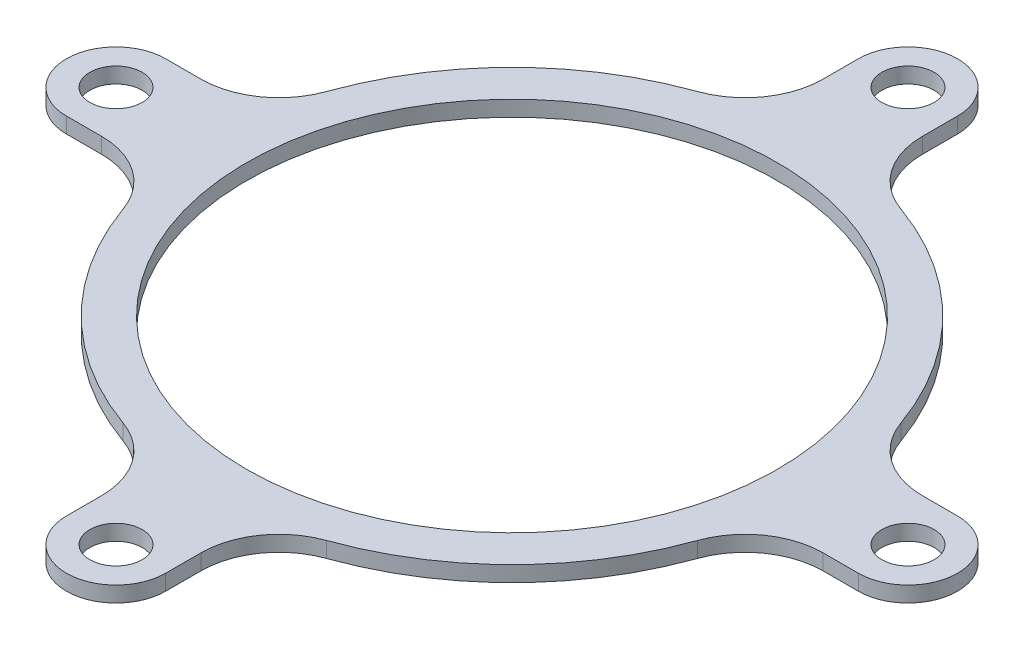
SolidWorks part; units mm, degrees
ref_plane "Front Plane" through (0, 0, 0) normal (0, 0, 1) x (1, 0, 0)
ref_plane "Top Plane" through (0, 0, 0) normal (0, 1, 0) x (1, 0, 0)
ref_plane "Right Plane" through (0, 0, 0) normal (1, 0, 0) x (0, 0, -1)
sketch "Sketch1" plane through (0, 0, 0) normal (0, 1, 0) x (1, 0, 0)
  circle A0 centre (0, 0) radius 34
  circle A1 centre (0, 0) radius 39
  dimension "innerDiam" = 68
  dimension "outerDiam" = 78
extrude "Boss-Extrude1" add sketch "Sketch1" along normal mid plane 2
sketch "Sketch2" plane through (0, 1, 0) normal (0, 1, 0) x (1, 0, 0)
  line L0 (0, 0) -> (0, 38.8704) construction
  line L1 (-6.35, 46.1917) -> (-6.35, 50.7)
  line L2 (6.35, 50.7) -> (6.35, 46.1917)
  arc A0 (-6.35, 50.7) -> (6.35, 50.7) centre (0, 50.7) cw
  arc A1 (6.35, 46.1917) -> (13.0133, 36.7649) centre (16.35, 46.1917) ccw
  circle A2 centre (0, 0) radius 39 construction
  arc A3 (-6.35, 46.1917) -> (-13.0133, 36.7649) centre (-16.35, 46.1917) cw
  arc A4 (13.0133, 36.7649) -> (-13.0133, 36.7649) centre (0, 0) ccw
  circle A5 centre (0, 0) radius 50.7 construction
  circle A6 centre (0, 50.7) radius 3.35
  dimension "supportsDiam" = 101.4
  dimension "rodDiam" = 6.7
  dimension "D3" = 3
  dimension "D4" = 10
extrude "Boss-Extrude2" add sketch "Sketch2" against normal up to surface (2 mm away) up to face at (0, -1, 39)
pattern_circular "CirPattern1" count 4 over 360 about axis through (0, 0, 0) along (0, 1, 0) of "Boss-Extrude2"
